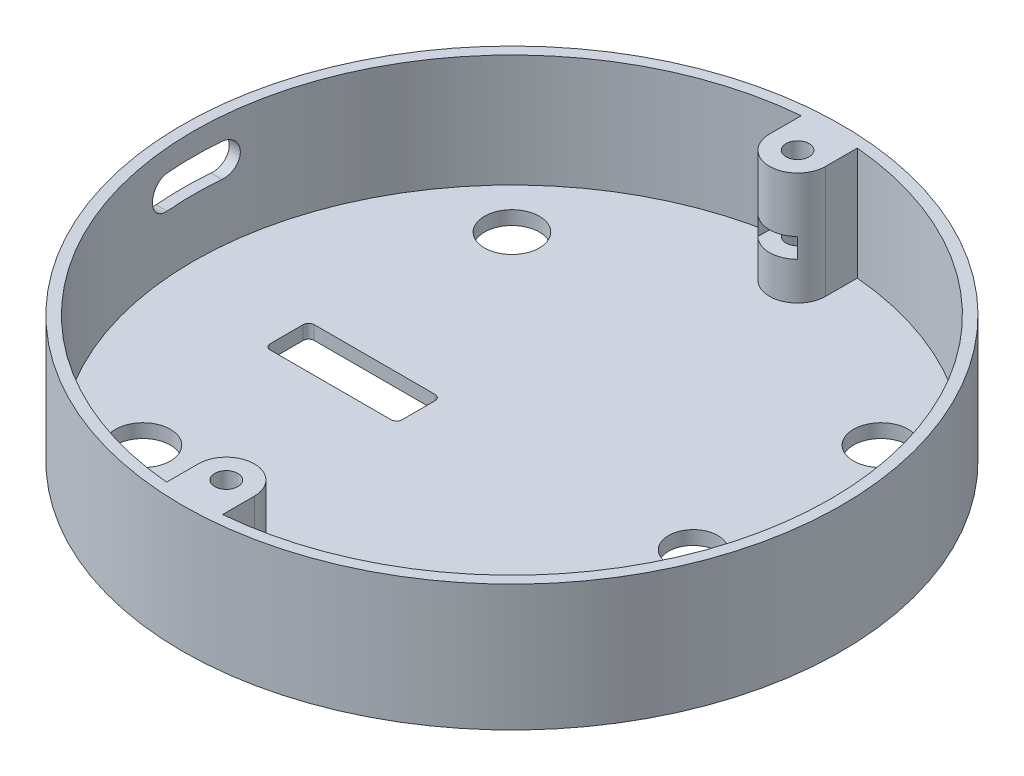
SolidWorks part; units mm, degrees
ref_plane "Front Plane" through (0, 0, 0) normal (0, 0, 1) x (1, 0, 0)
ref_plane "Top Plane" through (0, 0, 0) normal (0, 1, 0) x (1, 0, 0)
ref_plane "Right Plane" through (0, 0, 0) normal (1, 0, 0) x (0, 0, -1)
sketch "Sketch1" plane through (0, 0, 0) normal (0, 1, 0) x (1, 0, 0)
  circle A0 centre (0, 0) radius 60
  dimension "D1" = 120
extrude "Boss-Extrude1" add sketch "Sketch1" along normal blind 2.5
sketch "Sketch2" plane through (0, 2.5, 0) normal (0, 1, 0) x (1, 0, 0)
  circle A0 centre (0, 0) radius 58
  circle A1 centre (0, 0) radius 60
  circle A2 centre (0, 0) radius 60
  dimension "D1" = 0
  dimension "D2" = 2
extrude "Boss-Extrude2" add sketch "Sketch2" along normal blind 20.5
sketch "Sketch3" plane through (0, 2.5, 0) normal (0, 1, 0) x (1, 0, 0)
  line L0 (0, 0) -> (33, 0) construction
  line L1 (0, 0) -> (33.5876, 33.5876) construction
  circle A0 centre (33, 0) radius 4.5
  circle A1 centre (33.5876, 33.5876) radius 5
  circle A2 centre (33.5876, -33.5876) radius 5
  circle A3 centre (-33.5876, -33.5876) radius 5
  circle A4 centre (-33.5876, 33.5876) radius 5
  dimension "D4" = 9
  dimension "D5" = 10
  dimension "D1" = 45
  dimension "D2" = 47.5
  dimension "D3" = 33
  dimension "D6" = 4
extrude "Cut-Extrude1" cut sketch "Sketch3" against normal through all
sketch "Sketch4" plane through (0, 2.5, 0) normal (0, 1, 0) x (1, 0, 0)
  line L1 (-38, 1) -> (-14, 1)
  line L2 (-38, 1) -> (-38, -7)
  line L3 (-38, -7) -> (-14, -7)
  line L4 (-14, 1) -> (-14, -7)
  dimension "D1" = 14
  dimension "D2" = 24
  dimension "D3" = 8
  dimension "D4" = 1
extrude "Cut-Extrude2" cut sketch "Sketch4" against normal through all
fillet "Fillet1" radius 1 4 edges at (-14, 1.25, 7) (-38, 1.25, 7) (-14, 1.25, -1) (-38, 1.25, -1)
sketch "Sketch5" plane through (0, 2.5, 0) normal (0, 1, 0) x (1, 0, 0)
  line L0 (0, -52) -> (0, 52) construction
  line L1 (-5.1, 52) -> (-5.1, 57.7753)
  line L2 (5.1, 52) -> (5.1, 57.7753)
  line L3 (0, 0) -> (18.3005, 0) construction
  line L4 (5.1, -52) -> (5.1, -57.7753)
  line L5 (-5.1, -52) -> (-5.1, -57.7753)
  circle A0 centre (0, 52) radius 2.1
  arc A1 (-5.1, 52) -> (5.1, 52) centre (0, 52) ccw
  circle A2 centre (0, 0) radius 58 construction
  arc A3 (5.1, 57.7753) -> (-5.1, 57.7753) centre (0, 0) ccw
  circle A4 centre (0, 52) radius 5.1 construction
  arc A5 (5.1, -57.7753) -> (-5.1, -57.7753) centre (0, 0) cw
  arc A6 (-5.1, -52) -> (5.1, -52) centre (0, -52) cw
  circle A7 centre (0, -52) radius 2.1
  dimension "D2" = 4.2
  dimension "D1" = 52
  dimension "D3" = 3
extrude "Boss-Extrude3" add sketch "Sketch5" along normal through all
ref_plane "Plane1" through (0, 13, 0) normal (0, 1, 0) x (1, 0, 0)
sketch "Sketch6" plane through (0, 13, 0) normal (0, 1, 0) x (1, 0, 0)
  line L0 (0, 0) -> (7.9982, 0) construction
  line L1 (3.6, 54.0785) -> (0, 56.1569)
  line L2 (0, 56.1569) -> (-3.6, 54.0785)
  line L3 (-3.6, 54.0785) -> (-3.6, 48.3875)
  line L6 (3.6, 48.3875) -> (3.6, 54.0785)
  line L7 (-1.8, 48.8823) -> (0, 47.8431) [skipped]
  line L8 (1.8, 48.8823) -> (3.6, 49.9215) [skipped]
  line L9 (3.6, -48.3875) -> (3.6, -54.0785)
  line L10 (-3.6, -54.0785) -> (-3.6, -48.3875)
  line L11 (0, -56.1569) -> (-3.6, -54.0785)
  line L12 (3.6, -54.0785) -> (0, -56.1569)
  circle A0 centre (0, 52) radius 3.6 construction
  arc A1 (-5.1, 52) -> (5.1, 52) centre (0, 52) ccw construction
  arc A2 (-3.6, 48.3875) -> (3.6, 48.3875) centre (0, 52) ccw
  circle A3 centre (0, -52) radius 3.6 construction
  arc A4 (-3.6, -48.3875) -> (3.6, -48.3875) centre (0, -52) cw
  dimension "D1" = 7.2
extrude "Cut-Extrude3" cut sketch "Sketch6" against normal blind 3.6
ref_plane "Plane2" through (-60, 0, 0) normal (-1, 0, 0) x (0, 0, 1)
sketch "Sketch7" plane through (-60, 0, 0) normal (-1, 0, 0) x (0, 0, 1)
  line L0 (-5, 16) -> (5, 16) construction
  line L1 (-5, 19) -> (5, 19)
  line L2 (-5, 13) -> (5, 13)
  line L3 (60, 23) -> (-60, 23) construction
  arc A0 (-5, 19) -> (-5, 13) centre (-5, 16) ccw
  arc A1 (5, 13) -> (5, 19) centre (5, 16) ccw
  point P2 (0, 16)
  point P7 (0, 0)
  dimension "D1" = 3
  dimension "D2" = 10
  dimension "D3" = 4
extrude "Cut-Extrude4" cut sketch "Sketch7" against normal up to next
